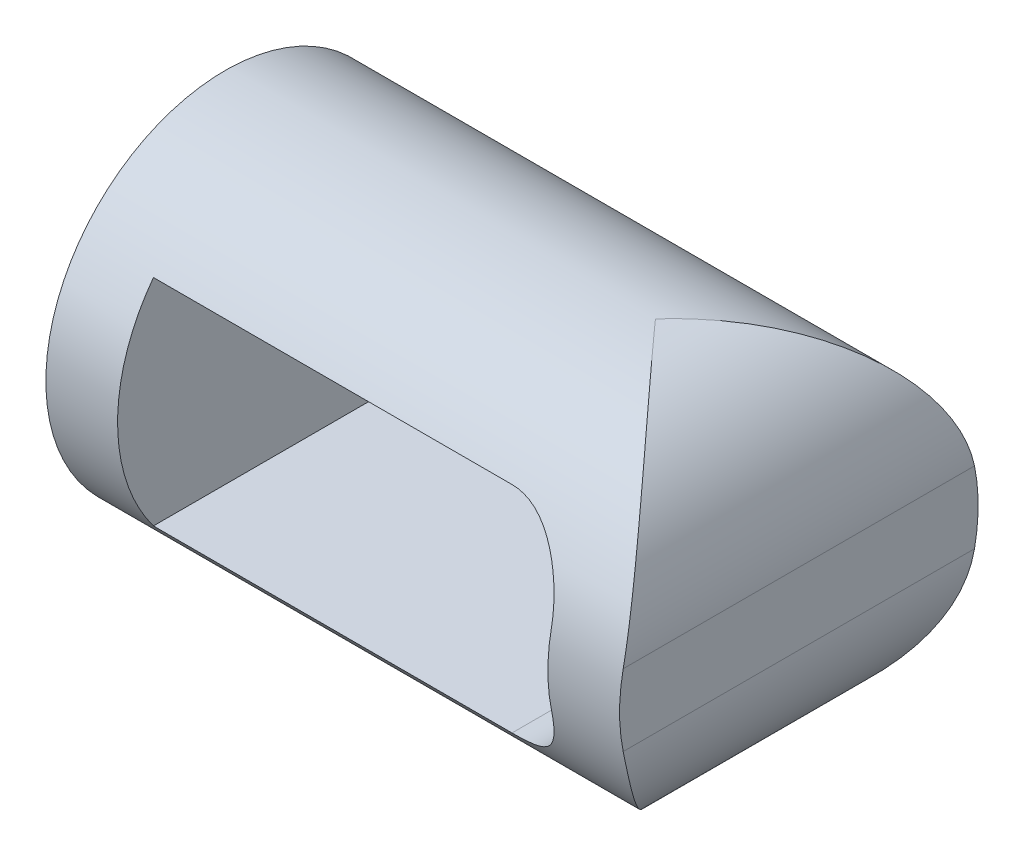
SolidWorks part; units mm, degrees
ref_plane "Front Plane" through (0, 0, 0) normal (0, 0, 1) x (1, 0, 0)
ref_plane "Top Plane" through (0, 0, 0) normal (0, 1, 0) x (1, 0, 0)
ref_plane "Right Plane" through (0, 0, 0) normal (1, 0, 0) x (0, 0, -1)
sketch "Sketch1" plane through (0, 0, 0) normal (1, 0, 0) x (0, 0, -1)
  circle A1 centre (0, 0) radius 12.5
  dimension "D2" = 25
extrude "Boss-Extrude4" add sketch "Sketch1" along normal blind 40 contours A1
sketch "Sketch2" plane through (0, 0, 0) normal (0, 0, 1) x (1, 0, 0)
  line L0 (0, 0) -> (5, 0)
  line L1 (13.75, 0) -> (-13.75, 0) construction
  line L2 (5, 0) -> (5, 7.5)
  line L3 (5, 0) -> (5, -7.5)
  line L4 (5, 7.5) -> (30, 7.5)
  line L5 (5, -7.5) -> (30, -7.5)
  line L7 (35, 2.5) -> (35, -2.5)
  arc A0 (30, 7.5) -> (35, 2.5) centre (30, 2.5) cw
  arc A1 (30, -7.5) -> (35, -2.5) centre (30, -2.5) ccw
  point P11 (35, 7.5)
  point P14 (35, -7.5)
  dimension "D6" = 5
  dimension "D7" = 5
  dimension "D10" = 25
  dimension "D1" = 5
  dimension "D2" = 7.5
  dimension "D3" = 7.5
  dimension "D4" = 30
  dimension "D5" = 30
extrude "Cut-Extrude2" cut sketch "Sketch2" against normal through all both and the other way through all contours L2 L4 A0 L7 A1 L5 L3
sketch "Sketch4" plane through (0, 0, 0) normal (0, 0, 1) x (1, 0, 0)
  line L10 (30, 12.5) -> (40, 12.5)
  line L11 (40, 12.5) -> (40, 2.5)
  arc A0 (40, 2.5) -> (30, 12.5) centre (30, 2.5) ccw
  point P15 (40, 12.5)
  point P18 (40, -12.5)
  dimension "D6" = 10
  dimension "D1" = 25
  dimension "D10" = 10
  dimension "D11" = 10
extrude "Cut-Extrude6" cut sketch "Sketch4" against normal through all both and the other way through all contours A0 L10 L11
sketch "Sketch5" plane through (0, 0, 0) normal (0, 0, 1) x (1, 0, 0)
  line L3 (30, -12.5) -> (40, -12.5)
  line L4 (40, -12.5) -> (40, -2.5)
  arc A0 (30, -12.5) -> (40, -2.5) centre (30, -2.5) ccw
  point P16 (40, -12.5)
  dimension "D1" = 10
  dimension "D2" = 10
  dimension "D3" = 10
extrude "Cut-Extrude7" cut sketch "Sketch5" against normal through all both and the other way through all contours A0 L4 L3
